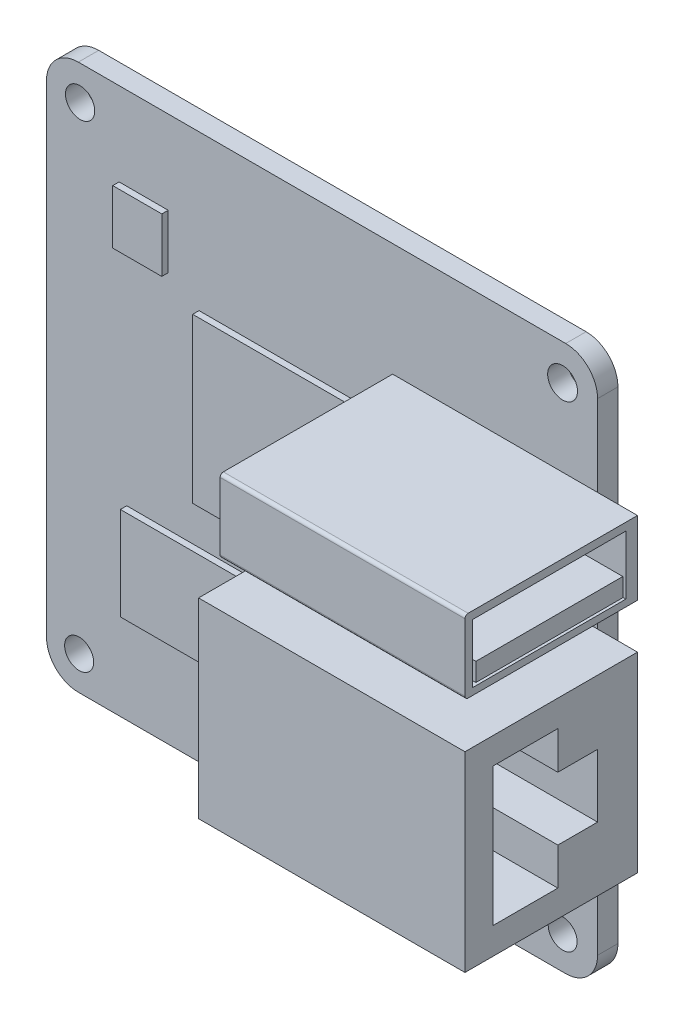
SolidWorks part; units mm, degrees
ref_plane "Plan de face" through (0, 0, 0) normal (0, 0, 1) x (1, 0, 0)
ref_plane "Plan de dessus" through (0, 0, 0) normal (0, 1, 0) x (1, 0, 0)
ref_plane "Plan de droite" through (0, 0, 0) normal (1, 0, 0) x (0, 0, -1)
sketch "plaque" plane through (0, 0, 0) normal (0, 0, 1) x (1, 0, 0)
  line L0 (3.1359, 126.4858) -> (46.3359, 126.4858) construction
  line L1 (3.1205, 98.2075) -> (3.1205, 137.6937) construction
  line L2 (46.4003, 96.103) -> (46.4003, 137.9429) construction
  line L4 (43.9003, 135.7554) -> (5.6205, 135.7554)
  line L5 (46.4003, 133.2554) -> (46.4003, 95.391)
  line L6 (43.9003, 92.891) -> (5.6205, 92.891)
  line L7 (3.1205, 133.2554) -> (3.1205, 95.391)
  arc A0 (5.6205, 92.891) -> (3.1205, 95.391) centre (5.6205, 95.391) cw
  arc A1 (46.4003, 95.391) -> (43.9003, 92.891) centre (43.9003, 95.391) cw
  arc A2 (43.9003, 135.7554) -> (46.4003, 133.2554) centre (43.9003, 133.2554) cw
  arc A3 (5.6205, 135.7554) -> (3.1205, 133.2554) centre (5.6205, 133.2554) ccw
  point P16 (46.4003, 135.7554)
  dimension "D2" = 2.5
  dimension "D1" = 43.2
sketch "usb" plane through (0, 0, 0) normal (0, 0, 1) x (1, 0, 0)
  line L1 (30.3065, 126.8746) -> (49.5362, 126.8746)
  line L2 (30.3065, 126.8746) -> (30.3065, 121.1057)
  line L3 (30.3065, 121.1057) -> (49.5362, 121.1057)
  line L4 (49.5362, 126.8746) -> (49.5362, 121.1057)
  line L5 (28.6125, 117.5803) -> (49.5362, 117.5803)
  line L6 (28.6125, 117.5803) -> (28.6125, 102.5628)
  line L7 (28.6125, 102.5628) -> (49.5362, 102.5628)
  line L8 (49.5362, 117.5803) -> (49.5362, 102.5628)
sketch "Esquisse3" plane through (0, 0, 0) normal (0, 0, 1) x (1, 0, 0)
  circle A0 centre (5.7595, 133.0709) radius 1.1489
  circle A1 centre (5.6832, 95.5393) radius 1.1408
  circle A2 centre (43.653, 132.9612) radius 1.1725
  circle A3 centre (43.6598, 95.5062) radius 1.1348
sketch "composants" plane through (0, 0, 0) normal (0, 0, 1) x (1, 0, 0)
  line L1 (15.1018, 123.5912) -> (27.96, 123.5912)
  line L2 (15.1018, 123.5912) -> (15.1018, 110.733)
  line L3 (15.1018, 110.733) -> (27.96, 110.733)
  line L4 (27.96, 123.5912) -> (27.96, 110.733)
  line L5 (9.4203, 107.4769) -> (22.2453, 107.4769)
  line L6 (9.4203, 107.4769) -> (9.4203, 100.1674)
  line L7 (9.4203, 100.1674) -> (22.2453, 100.1674)
  line L8 (22.2453, 107.4769) -> (22.2453, 100.1674)
  line L9 (8.8222, 129.2063) -> (12.6764, 129.2063)
  line L10 (8.8222, 129.2063) -> (8.8222, 124.9535)
  line L11 (8.8222, 124.9535) -> (12.6764, 124.9535)
  line L12 (12.6764, 129.2063) -> (12.6764, 124.9535)
extrude "Boss.-Extru.1" add sketch "plaque" against normal blind 1.6
extrude "Enlèv. mat.-Extru.1" cut sketch "Esquisse3" against normal blind 1.6
extrude "Boss.-Extru.2" add sketch "composants" along normal blind 0.5
extrude "Boss.-Extru.3" add sketch "usb" along normal blind 13.55
sketch "Esquisse6" plane through (49.5362, 0, 0) normal (1, 0, 0) x (0, 0, -1)
  line L1 (-11.3355, 104.657) -> (-6.2549, 104.657)
  line L2 (-11.3355, 104.657) -> (-11.3355, 115.5072)
  line L3 (-11.3355, 115.5072) -> (-6.2549, 115.5072)
  line L4 (-6.2549, 104.657) -> (-6.2549, 115.5072)
extrude "Enlèv. mat.-Extru.2" cut sketch "Esquisse6" against normal blind 13.55
sketch "Esquisse7" plane through (49.5362, 0, 0) normal (1, 0, 0) x (0, 0, -1)
  line L0 (-6.2549, 104.657) -> (-6.2549, 115.5072) construction
  line L1 (-6.2549, 107.5848) -> (-3.1333, 107.5848)
  line L2 (-6.2549, 107.5848) -> (-6.2549, 112.5363)
  line L3 (-6.2549, 112.5363) -> (-3.1333, 112.5363)
  line L4 (-3.1333, 107.5848) -> (-3.1333, 112.5363)
extrude "Enlèv. mat.-Extru.3" cut sketch "Esquisse7" against normal blind 13.55
sketch "Esquisse8" plane through (49.5362, 0, 0) normal (1, 0, 0) x (0, 0, -1)
  line L1 (-12.9502, 121.6428) -> (-0.9159, 121.6428)
  line L2 (-12.9502, 121.6428) -> (-12.9502, 126.2714)
  line L3 (-12.9502, 126.2714) -> (-0.9159, 126.2714)
  line L4 (-0.9159, 121.6428) -> (-0.9159, 126.2714)
extrude "Enlèv. mat.-Extru.4" cut sketch "Esquisse8" against normal blind 13.55
sketch "Esquisse9" plane through (35.9862, 0, 0) normal (1, 0, 0) x (0, 0, -1)
  line L1 (-12.6918, 121.8581) -> (-1.1527, 121.8581)
  line L2 (-12.6918, 121.8581) -> (-12.6918, 123.3005)
  line L3 (-12.6918, 123.3005) -> (-1.1527, 123.3005)
  line L4 (-1.1527, 121.8581) -> (-1.1527, 123.3005)
extrude "Boss.-Extru.4" add sketch "Esquisse9" along normal blind 13.55
fillet "Congé1" radius 0.25 2 edges at (39.9214, 126.8746, 13.55) (39.9214, 121.1057, 13.55)
